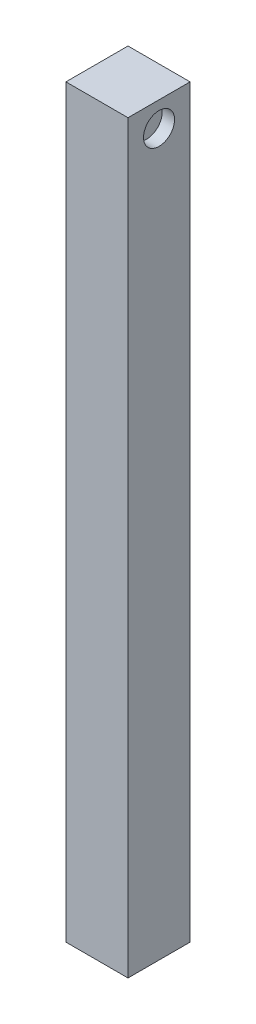
SolidWorks part; units mm, degrees
ref_plane "Front Plane" through (0, 0, 0) normal (0, 0, 1) x (1, 0, 0)
ref_plane "Top Plane" through (0, 0, 0) normal (0, 1, 0) x (1, 0, 0)
ref_plane "Right Plane" through (0, 0, 0) normal (1, 0, 0) x (0, 0, -1)
sketch "Sketch1" plane through (0, 0, 0) normal (1, 0, 0) x (0, 0, -1)
  line L1 (-50, -600) -> (50, -600)
  line L2 (-50, -600) -> (-50, 600)
  line L3 (-50, 600) -> (50, 600)
  line L4 (50, -600) -> (50, 600)
  line L5 (-50, -600) -> (50, 600) construction
  line L6 (-50, 600) -> (50, -600) construction
  point P0 (0, 0)
  dimension "D1" = 100
  dimension "D2" = 1200
extrude "Boss-Extrude1" add sketch "Sketch1" along normal mid plane 100
sketch "Sketch2" plane through (50, 0, 0) normal (1, 0, 0) x (0, 0, -1)
  line L0 (0, 600) -> (0, 0) construction
  line L1 (50, 600) -> (-50, 600) construction
  circle A0 centre (0, 560) radius 25
  dimension "D1" = 50
  dimension "D2" = 40
extrude "Cut-Extrude1" cut sketch "Sketch2" against normal blind 20
